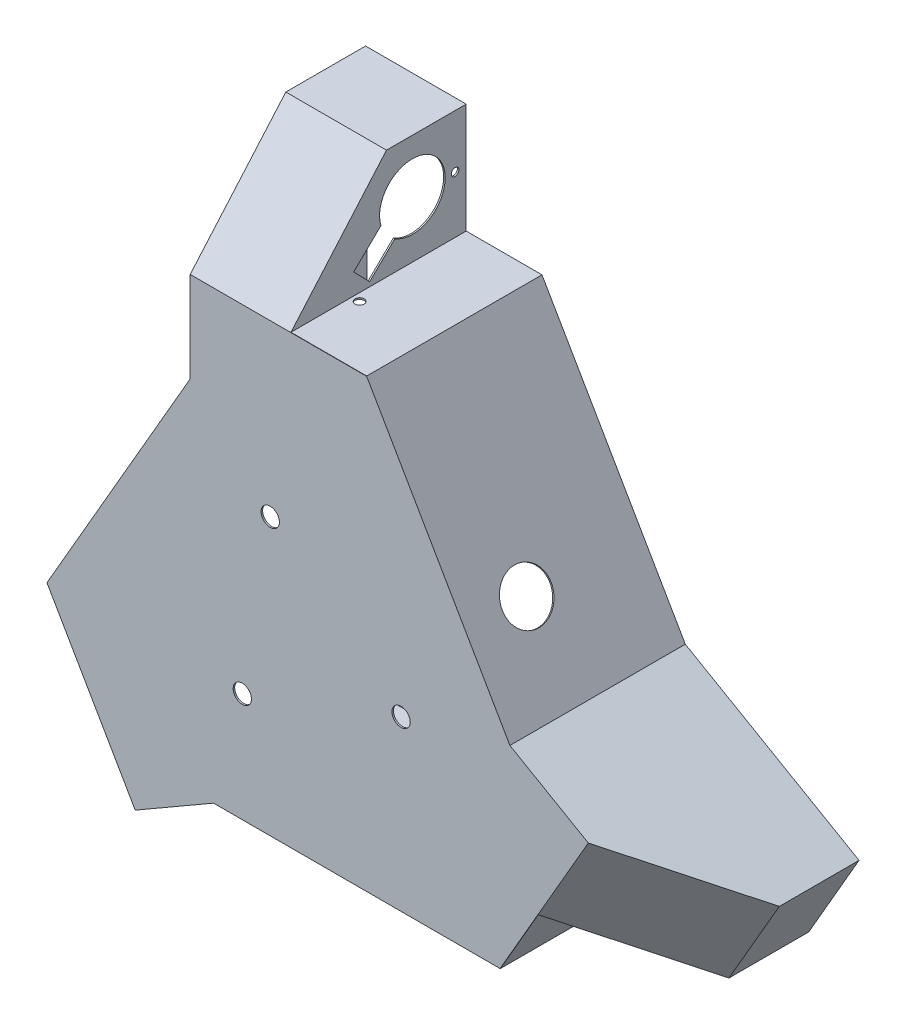
SolidWorks part; units mm, degrees
ref_plane "前视基准面" through (0, 0, 0) normal (0, 0, 1) x (1, 0, 0)
ref_plane "上视基准面" through (0, 0, 0) normal (0, 1, 0) x (1, 0, 0)
ref_plane "右视基准面" through (0, 0, 0) normal (1, 0, 0) x (0, 0, -1)
sketch "草图1" plane through (0, 0, 0) normal (0, 0, 1) x (1, 0, 0)
  circle A0 centre (0, 0) radius 255
  dimension "D1" = 510
extrude "拉伸1" add sketch "草图1" along normal blind 115
sketch "草图2" plane through (0, 0, 115) normal (0, 0, 1) x (1, 0, 0)
  line L0 (0, 0) -> (0, 49000) construction
  line L1 (-75, 243.7212) -> (-75, 112.1688)
  line L2 (-866.0254, -500) -> (0, 0) construction
  line L3 (866.0254, -500) -> (0, 0) construction
  line L5 (-149.641, -17.1132) -> (-168.971, -50.5937)
  line L6 (134.641, 8.8675) -> (248.5687, -56.9087)
  line L7 (-173.5687, -186.8125) -> (-59.641, -121.0363)
  line L8 (60, 138.1495) -> (40.6701, 171.63)
  line L9 (-30, 150.1111) -> (30, 150.1111) construction
  line L10 (30, 150.1111) -> (145, -49.0748) construction
  line L11 (145, -49.0748) -> (115, -101.0363) construction
  line L12 (115, -101.0363) -> (-115, -101.0363) construction
  line L13 (-115, -101.0363) -> (-145, -49.0748) construction
  line L14 (-145, -49.0748) -> (-30, 150.1111) construction
  line L15 (-115, 2.8868) -> (-60, 98.1495) construction
  line L16 (-55, -101.0363) -> (55, -101.0363) construction
  line L17 (115, 2.8868) -> (60, 98.1495) construction
  line L18 (-216.1989, -135.2148) -> (-144.1359, -93.6092)
  line L19 (-144.1359, -93.6092) -> (-168.971, -50.5937)
  line L20 (225.1989, -119.6263) -> (153.1359, -78.0208)
  line L21 (153.1359, -78.0208) -> (128.3009, -121.0363)
  line L22 (-9, 254.8411) -> (-9, 171.63)
  line L23 (-9, 171.63) -> (40.6701, 171.63)
  line L24 (-75, 112.1688) -> (-149.641, -17.1132)
  line L25 (60, 138.1495) -> (134.641, 8.8675)
  line L26 (-59.641, -121.0363) -> (89.641, -121.0363)
  line L27 (89.641, -121.0363) -> (128.3009, -121.0363)
  circle A0 centre (0, 0) radius 255 construction
  arc A1 (-75, 243.7212) -> (-216.1989, -135.2148) centre (0, 0) ccw
  arc A2 (248.5687, -56.9087) -> (-9, 254.8411) centre (0, 0) ccw
  arc A3 (-173.5687, -186.8125) -> (225.1989, -119.6263) centre (0, 0) ccw
  dimension "D6" = 75
  dimension "D1" = 75
  dimension "D3" = 171.63
  dimension "D4" = 75
  dimension "D7" = 230
  dimension "D8" = 60
  dimension "D9" = 230
  dimension "D10" = 60
  dimension "D11" = 60
  dimension "D12" = 230
  dimension "D13" = 30
  dimension "D14" = 30
  dimension "D15" = 9
  dimension "D16" = 9
  dimension "D17" = 9
  dimension "D18" = 171.63
  dimension "D19" = 20
  dimension "D20" = 171.63
  dimension "D21" = 20
  dimension "D22" = 20
extrude "切除-拉伸1" cut sketch "草图2" against normal through all
sketch "草图3" plane through (0, 0, 115) normal (0, 0, 1) x (1, 0, 0)
  line L0 (225.1989, -119.6263) -> (153.1359, -78.0208) construction
  line L1 (225.1989, -119.6263) -> (215.5687, -114.0663)
  line L2 (-9, 254.8411) -> (-9, 171.63) construction
  line L3 (-216.1989, -135.2148) -> (-144.1359, -93.6092) construction
  line L4 (-9, 254.8411) -> (-9, 243.7212)
  line L5 (-216.1989, -135.2148) -> (-206.5687, -129.6548)
  line L6 (-75, 243.7212) -> (-9, 243.7212)
  line L7 (-173.5687, -186.8125) -> (-206.5687, -129.6548)
  line L8 (248.5687, -56.9087) -> (215.5687, -114.0663)
  arc A0 (-9, 254.8411) -> (-75, 243.7212) centre (0, 0) ccw construction
  arc A1 (-9, 254.8411) -> (-75, 243.7212) centre (0, 0) ccw
  arc A2 (-216.1989, -135.2148) -> (-173.5687, -186.8125) centre (0, 0) ccw construction
  arc A3 (-216.1989, -135.2148) -> (-173.5687, -186.8125) centre (0, 0) ccw
  arc A4 (225.1989, -119.6263) -> (248.5687, -56.9087) centre (0, 0) ccw construction
  arc A5 (225.1989, -119.6263) -> (248.5687, -56.9087) centre (0, 0) ccw
extrude "切除-拉伸2" cut sketch "草图3" against normal blind 140
sketch "草图4" plane through (37.5, -64.9519, 0) normal (0.5, -0.866, 0) x (0.866, 0.5, 0)
  line L0 (-112.1688, 115) -> (-243.7212, 115) construction
  line L1 (-171.5212, 115) -> (-243.7212, 115)
  line L2 (-243.7212, 0) -> (-243.7212, 115) construction
  line L3 (-243.7212, 52.2817) -> (-243.7212, 115)
  line L4 (-171.5212, 115) -> (-243.7212, 52.2817)
  dimension "D1" = 139.02
  dimension "D2" = 72.2
extrude "切除-拉伸3" cut sketch "草图4" against normal blind 140
sketch "草图5" plane through (37.5, 64.9519, 0) normal (0.5, 0.866, 0) x (-0.866, 0.5, 0)
  line L0 (-112.1688, 115) -> (-243.7212, 115) construction
  line L1 (-171.5212, 115) -> (-243.7212, 115)
  line L2 (-243.7212, 0) -> (-243.7212, 115) construction
  line L3 (-243.7212, 52.2817) -> (-243.7212, 115)
  line L4 (-171.5212, 115) -> (-243.7212, 52.2817)
  dimension "D1" = 139.02
  dimension "D2" = 72.2
extrude "切除-拉伸4" cut sketch "草图5" against normal blind 140
sketch "草图6" plane through (-75, 0, 0) normal (-1, 0, 0) x (0, 0, 1)
  line L0 (115, 112.1688) -> (115, 243.7212) construction
  line L1 (115, 171.5212) -> (115, 243.7212)
  line L2 (0, 243.7212) -> (115, 243.7212) construction
  line L3 (52.2817, 243.7212) -> (115, 243.7212)
  line L4 (115, 171.5212) -> (52.2817, 243.7212)
  dimension "D1" = 72.2
  dimension "D2" = 139.02
extrude "切除-拉伸5" cut sketch "草图6" against normal blind 140
shell "抽壳1" thickness 1
sketch "草图7" plane through (-9, 0, 0) normal (1, 0, 0) x (0, 0, -1)
  line L0 (0, 243.7212) -> (0, 171.63) construction
  line L1 (0, 243.7212) -> (-52.2817, 243.7212) construction
  line L2 (-20.0972, 224.0339) -> (34612.9323, 34857.0634) construction
  arc A0 (-45.9904, 190.1773) -> (-56.3459, 204.4359) centre (-35.3, 208.8312) ccw construction
  arc A1 (-56.3459, 204.4359) -> (-45.9904, 190.1773) centre (-35.3, 208.8312) ccw construction
  circle A2 centre (-35.3, 208.8312) radius 21.5
  dimension "D3" = 43
  dimension "D1" = 35.3
  dimension "D2" = 34.89
extrude "切除-拉伸6" cut sketch "草图7" against normal blind 10
sketch "草图8" plane through (4.5, 7.7942, 0) normal (-0.5, -0.866, 0) x (0.866, -0.5, 0)
  line L0 (243.7212, 0) -> (171.63, 0) construction
  line L1 (243.7212, 0) -> (243.7212, 52.2817) construction
  line L2 (915.9379, -671.8068) -> (-34439.4011, 34683.5323) construction
  line L3 (202.444, 55.8293) -> (184.7895, 73.4838)
  line L4 (184.7895, 73.4838) -> (174.1829, 62.8772)
  line L5 (174.1829, 62.8772) -> (190.5096, 46.5504)
  arc A0 (190.5096, 46.5504) -> (202.444, 55.8293) centre (208.8312, 35.3) ccw
  dimension "D3" = 43
  dimension "D1" = 35.3
  dimension "D2" = 34.89
  dimension "D4" = 44
  dimension "D5" = 5
  dimension "D6" = 10
extrude "切除-拉伸7" cut sketch "草图8" against normal blind 10
sketch "草图9" plane through (4.5, -7.7942, 0) normal (-0.5, 0.866, 0) x (-0.866, -0.5, 0)
  line L0 (243.7212, 0) -> (171.63, 0) construction
  line L1 (243.7212, 0) -> (243.7212, 52.2817) construction
  line L2 (915.9379, -671.8068) -> (-34439.4011, 34683.5323) construction
  line L3 (202.444, 55.8293) -> (184.7895, 73.4838)
  line L4 (184.7895, 73.4838) -> (174.1829, 62.8772)
  line L5 (174.1829, 62.8772) -> (190.5096, 46.5504)
  arc A0 (190.5096, 46.5504) -> (202.444, 55.8293) centre (208.8312, 35.3) ccw
  point P4 (243.7212, 26.1409)
  dimension "D3" = 43
  dimension "D1" = 35.3
  dimension "D2" = 34.89
  dimension "D4" = 44
  dimension "D5" = 5
  dimension "D6" = 10
extrude "切除-拉伸8" cut sketch "草图9" against normal blind 10
sketch "草图10" plane through (0, 0, 115) normal (0, 0, 1) x (1, 0, 0)
  circle A1 centre (-22.5, 60.1111) radius 6
  circle A2 centre (-40.8077, -49.5411) radius 6
  circle A4 centre (63.3077, -10.57) radius 6
  dimension "D1" = 12
extrude "切除-拉伸9" cut sketch "草图10" against normal blind 10
sketch "草图11" plane through (-9, 0, 0) normal (1, 0, 0) x (0, 0, -1)
  circle A0 centre (-7.3043, 208.8328) radius 2.5
  dimension "D1" = 5
sketch "草图12" plane through (4.5, 7.7942, 0) normal (-0.5, -0.866, 0) x (0.866, -0.5, 0)
  circle A0 centre (208.8328, 7.3043) radius 2.5
  dimension "D1" = 5
sketch "草图13" plane through (4.5, -7.7942, 0) normal (-0.5, 0.866, 0) x (-0.866, -0.5, 0)
  circle A0 centre (208.8328, 7.3043) radius 2.5
  dimension "D1" = 5
extrude "切除-拉伸10" cut sketch "草图11" against normal blind 10
extrude "切除-拉伸11" cut sketch "草图13" against normal blind 10
extrude "切除-拉伸12" cut sketch "草图12" against normal blind 10
sketch "草图16" plane through (104.8205, 60.5181, 0) normal (0.866, 0.5, 0) x (0, 0, -1)
  line L0 (0, 128.3009) -> (-114.9054, 128.3009) construction
  line L1 (-115, 128.1752) -> (-115, -59.641) construction
  circle A0 centre (-75, -1.6991) radius 16
  dimension "D1" = 32
  dimension "D2" = 130
  dimension "D3" = 40
extrude "切除-拉伸13" cut sketch "草图16" against normal blind 4.5
sketch "草图17" plane through (-9, 0, 0) normal (1, 0, 0) x (0, 0, -1)
  line L0 (-750.9612, -489.0868) -> (35032.101, 34406.8088) construction
  line L1 (-55.9079, 202.7021) -> (-73.7825, 185.2707)
  line L2 (-73.7825, 185.2707) -> (-63.3099, 174.5318)
  line L3 (-63.3099, 174.5318) -> (-46.7795, 190.6523)
  circle A0 centre (-35.3, 208.8312) radius 21.5 construction
  arc A1 (-46.7795, 190.6523) -> (-55.9079, 202.7021) centre (-35.3, 208.8312) ccw
  dimension "D1" = 5
  dimension "D2" = 10
  dimension "D3" = 44
extrude "切除-拉伸14" cut sketch "草图17" against normal blind 4.5
sketch "草图18" plane through (0, 171.63, 0) normal (0, 1, 0) x (-1, 0, 0)
  line L1 (9, 114.9054) -> (-40.6701, 114.9054) construction
  line L2 (9, 0) -> (9, 114.9054) construction
  circle A0 centre (4, 74.9054) radius 3
  dimension "D1" = 6
  dimension "D2" = 40
  dimension "D3" = 5
extrude "切除-拉伸15" cut sketch "草图18" against normal blind 4.5
sketch "草图19" plane through (148.6359, -85.815, 0) normal (0.866, -0.5, 0) x (0, 0, -1)
  line L0 (-114.9054, 9) -> (-114.9054, -40.6701) construction
  line L1 (0, 9) -> (-114.9054, 9) construction
  circle A0 centre (-74.9054, 4) radius 3
  dimension "D3" = 6
  dimension "D1" = 40
  dimension "D2" = 5
extrude "切除-拉伸16" cut sketch "草图19" against normal blind 4.5
sketch "草图20" plane through (-148.6359, -85.815, 0) normal (-0.866, -0.5, 0) x (0, 0, 1)
  line L0 (114.9054, -9) -> (114.9054, 40.6701) construction
  line L1 (52.2817, -9) -> (114.9054, -9) construction
  circle A0 centre (74.9054, -4) radius 3
  dimension "D3" = 6
  dimension "D1" = 40
  dimension "D2" = 5
extrude "切除-拉伸17" cut sketch "草图20" against normal blind 4.5
sketch "草图23" plane through (0, -121.0363, 0) normal (0, -1, 0) x (1, 0, 0)
  line L0 (-41.141, 62.4332) -> (108.859, 62.4332) construction
  line L1 (-26.141, 22.8216) -> (93.859, 22.8216) construction
  line L4 (-59.641, 0) -> (-59.641, 115) construction
  text T0 "<i>Warsonco</i>" font "Century Gothic" height in points 48
  text T1 "华盛控科技" font "Century Gothic" height in points 42
  dimension "D1" = 150
  dimension "D2" = 18.5
  dimension "D3" = 120
  dimension "D4" = 15
extrude "拉伸3" [suppressed] add sketch "草图23" along normal blind 1
